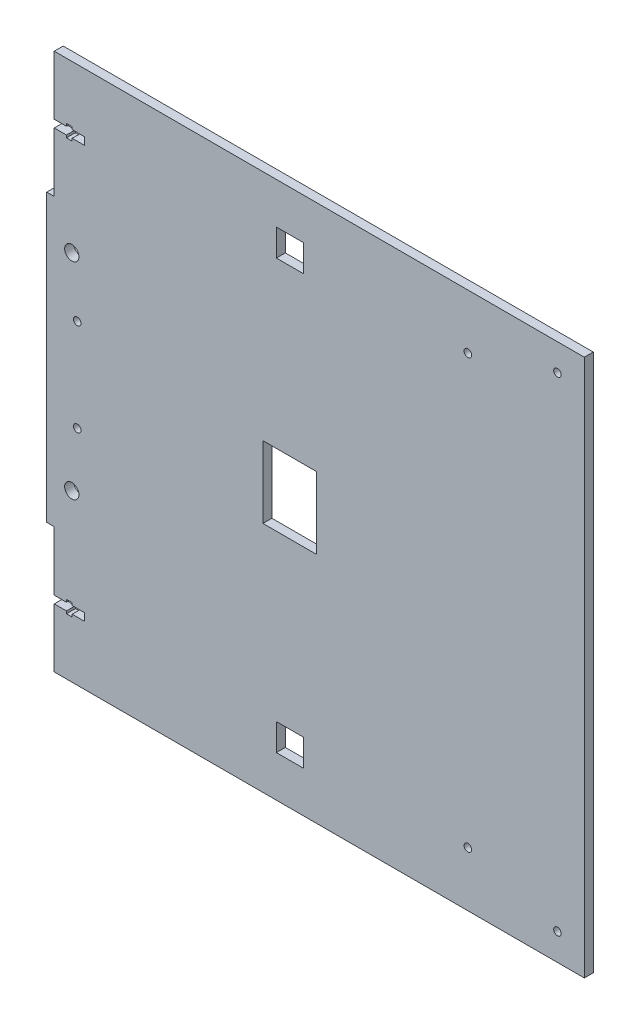
SolidWorks part; units mm, degrees
material "Balsa"
ref_plane "Plan de face" through (0, 0, 0) normal (0, 0, 1) x (1, 0, 0)
ref_plane "Plan de dessus" through (0, 0, 0) normal (0, 1, 0) x (1, 0, 0)
ref_plane "Plan de droite" through (0, 0, 0) normal (1, 0, 0) x (0, 0, -1)
sketch "Esquisse1" plane through (0, 0, 0) normal (0, 0, 1) x (1, 0, 0)
  line L1 (-150, -150) -> (150, -150)
  line L2 (-150, -150) -> (-150, 150)
  line L3 (-150, 150) -> (150, 150)
  line L4 (150, -150) -> (150, 150)
  line L5 (-150, -150) -> (150, 150) construction
  line L6 (-150, 150) -> (150, -150) construction
  point P0 (0, 0)
  dimension "D1" = 300
  dimension "D2" = 300
extrude "Boss.-Extru.1" add sketch "Esquisse1" along normal blind 5
sketch "Esquisse4" plane through (-150, 0, 0) normal (-1, 0, 0) x (0, 0, 1)
  line L1 (0, 150) -> (5, 150)
  line L2 (0, 150) -> (0, 79.8)
  line L3 (0, 80) -> (5, 80) construction
  line L4 (5, 150) -> (5, 79.8)
  line L5 (5, 150) -> (5, -150) construction
  line L13 (0, 0) -> (5, 0) construction
  line L14 (0, 150) -> (0, -150) construction
  line L15 (5, 79.8) -> (0, 79.8)
  line L16 (0, -80) -> (5, -80) construction
  line L17 (5, -79.8) -> (0, -79.8)
  line L18 (5, -150) -> (5, -79.8)
  line L19 (0, -150) -> (0, -79.8)
  line L20 (0, -150) -> (5, -150)
  dimension "D1" = 0.2
  dimension "D2" = 70.2
extrude "Enlèv. mat.-Extru.3" cut sketch "Esquisse4" against normal blind 4.2
sketch "Esquisse7" plane through (0, 0, 5) normal (0, 0, 1) x (1, 0, 0)
  line L0 (0, 0) -> (150, 0) construction
  line L1 (150, -150) -> (150, 150) construction
  line L2 (-145.8, -150) -> (150, -150) construction
  circle A0 centre (135, -135) radius 2.1
  circle A1 centre (135, 135) radius 2.1
  dimension "D1" = 15
  dimension "D3" = 4.2
  dimension "D2" = 15
extrude "Enlèv. mat.-Extru.6" cut sketch "Esquisse7" against normal through all
sketch "Esquisse8" plane through (0, 0, 0) normal (0, 0, -1) x (-1, 0, 0)
  line L1 (29.346, -20) -> (-0.654, -20)
  line L2 (29.346, -20) -> (29.346, 20)
  line L3 (29.346, 20) -> (-0.654, 20)
  line L4 (-0.654, -20) -> (-0.654, 20)
extrude "Enlèv. mat.-Extru.7" cut sketch "Esquisse8" against normal through all
sketch "Esquisse9" plane through (0, 0, 0) normal (0, 0, -1) x (-1, 0, 0)
  line L0 (150, 79.8) -> (150, -79.8) construction
  line L2 (0, 0) -> (150, 0) construction
  line L3 (146, 37.5) -> (-100, 37.5) construction
  circle A0 centre (136, 57.5) radius 4
  circle A1 centre (136, -57.5) radius 4
  dimension "D1" = 8
  dimension "D2" = 14
  dimension "D3" = 20
extrude "Enlèv. mat.-Extru.8" cut sketch "Esquisse9" against normal through all
sketch "Esquisse10" plane through (0, 0, 0) normal (0, 0, -1) x (-1, 0, 0)
  line L0 (-87.1, 121.5) -> (-82.9, 117.5) construction
  line L1 (-82.9, 121.5) -> (-87.1, 117.5) construction
  line L2 (0, 0) -> (-150, 0) construction
  line L3 (-150, -150) -> (-150, 150) construction
  line L4 (-82.9, -121.5) -> (-87.1, -117.5) construction
  line L5 (-87.1, -121.5) -> (-82.9, -117.5) construction
  circle A0 centre (-85, 119.5) radius 2.1
  circle A1 centre (-85, -119.5) radius 2.1
  dimension "D1" = 4.2
extrude "Enlèv. mat.-Extru.9" cut sketch "Esquisse10" against normal through all
sketch "Esquisse11" plane through (0, 0, 0) normal (0, 0, -1) x (-1, 0, 0)
  line L0 (-30.4, 121.5) -> (35, 121.5) construction
  line L1 (21.846, 112) -> (6.846, 112)
  line L2 (21.846, 112) -> (21.846, 127)
  line L3 (21.846, 127) -> (6.846, 127)
  line L4 (6.846, 112) -> (6.846, 127)
  line L5 (21.846, 112) -> (6.846, 127) construction
  line L6 (21.846, 127) -> (6.846, 112) construction
  line L7 (-0.654, 20) -> (-0.654, -20) construction
  line L8 (-0.654, 0) -> (-150, 0) construction
  line L9 (-0.654, 20) -> (-0.654, -20) construction
  line L10 (-150, -150) -> (-150, 150) construction
  line L11 (21.846, -127) -> (6.846, -112) construction
  line L12 (21.846, -112) -> (6.846, -127) construction
  line L13 (6.846, -112) -> (6.846, -127)
  line L14 (21.846, -127) -> (6.846, -127)
  line L15 (21.846, -112) -> (21.846, -127)
  line L16 (21.846, -112) -> (6.846, -112)
  point P0 (14.346, 119.5)
  point P20 (14.346, -119.5)
  dimension "D1" = 2
  dimension "D2" = 15
  dimension "D3" = 15
  dimension "D4" = 15
extrude "Enlèv. mat.-Extru.10" cut sketch "Esquisse11" against normal through all
sketch "Esquisse12" plane through (0, 0, 0) normal (0, 0, -1) x (-1, 0, 0)
  line L0 (146, -117.1) -> (150, -112.9) construction
  line L1 (148, -115) -> (128.8, -115) construction
  line L2 (145.8, -115) -> (145.8, -117.1)
  line L3 (145.8, -79.8) -> (145.8, -150) construction
  line L4 (145.8, -117.1) -> (139, -117.1)
  line L5 (139, -117.1) -> (139, -118.5)
  line L6 (139, -118.5) -> (135.8, -118.5)
  line L7 (135.8, -118.5) -> (135.8, -117.1)
  line L8 (135.8, -117.1) -> (128.8, -117.1)
  line L9 (128.8, -117.1) -> (128.8, -112.9)
  line L10 (135.8, -112.9) -> (128.8, -112.9)
  line L11 (135.8, -111.5) -> (135.8, -112.9)
  line L12 (139, -111.5) -> (135.8, -111.5)
  line L13 (139, -112.9) -> (139, -111.5)
  line L14 (145.8, -112.9) -> (139, -112.9)
  line L15 (145.8, -115) -> (145.8, -112.9)
  line L16 (0, 0) -> (-150, 0) construction
  line L17 (-150, -150) -> (-150, 150) construction
  line L18 (148, 115) -> (128.8, 115) construction
  line L19 (146, 117.1) -> (150, 112.9) construction
  line L20 (145.8, 115) -> (145.8, 112.9)
  line L21 (145.8, 112.9) -> (139, 112.9)
  line L22 (139, 112.9) -> (139, 111.5)
  line L23 (139, 111.5) -> (135.8, 111.5)
  line L24 (135.8, 111.5) -> (135.8, 112.9)
  line L25 (135.8, 112.9) -> (128.8, 112.9)
  line L26 (128.8, 117.1) -> (128.8, 112.9)
  line L27 (135.8, 117.1) -> (128.8, 117.1)
  line L28 (135.8, 118.5) -> (135.8, 117.1)
  line L29 (139, 118.5) -> (135.8, 118.5)
  line L30 (139, 117.1) -> (139, 118.5)
  line L31 (145.8, 117.1) -> (139, 117.1)
  line L32 (145.8, 115) -> (145.8, 117.1)
  dimension "D1" = 7
  dimension "D2" = 4.2
  dimension "D3" = 10
  dimension "D4" = 17
  dimension "D5" = 3.2
extrude "Enlèv. mat.-Extru.11" cut sketch "Esquisse12" against normal through all
sketch "Esquisse13" plane through (0, 0, 0) normal (0, 0, -1) x (-1, 0, 0)
  line L0 (0, 0) -> (146, 0) construction
  line L1 (146, -70) -> (146, 70) construction
  circle A0 centre (132.95, 25.85) radius 2.1
  circle A1 centre (132.95, -25.85) radius 2.1
  dimension "D1" = 4.2
extrude "Enlèv. mat.-Extru.12" cut sketch "Esquisse13" against normal through all
